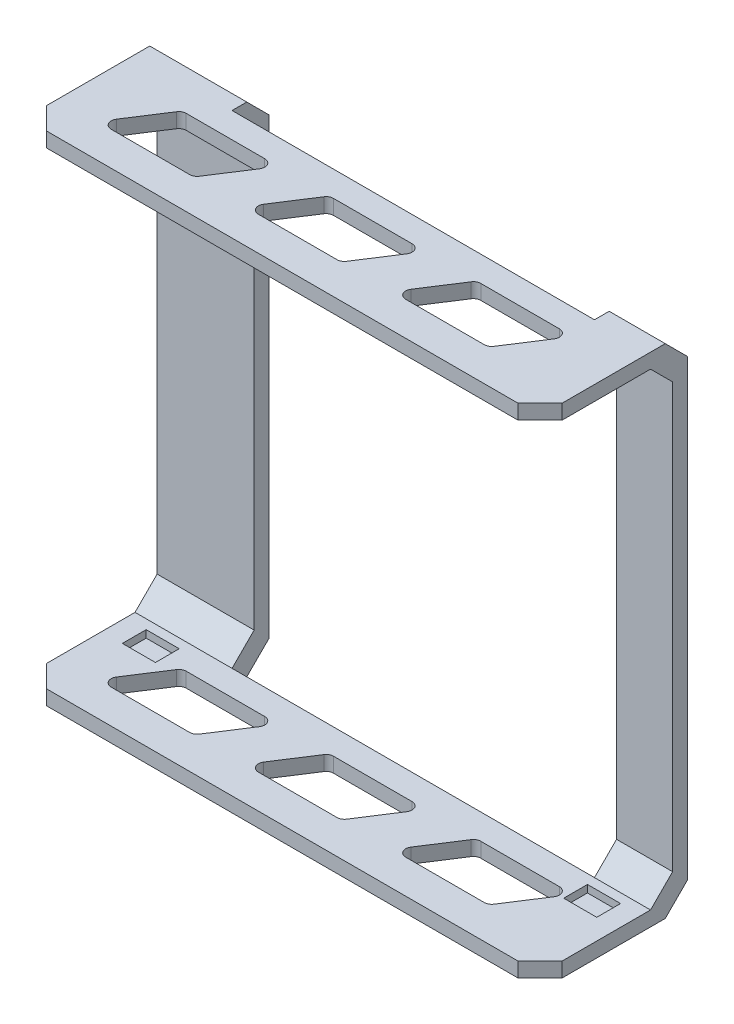
SolidWorks part; units mm, degrees
ref_plane "Front Plane" through (0, 0, 0) normal (0, 0, 1) x (1, 0, 0)
ref_plane "Top Plane" through (0, 0, 0) normal (0, 1, 0) x (1, 0, 0)
ref_plane "Right Plane" through (0, 0, 0) normal (1, 0, 0) x (0, 0, -1)
sketch "Sketch2" plane through (0, 0, 0) normal (0, 0, 1) x (1, 0, 0)
  line L1 (-34.5293, -31.742) -> (35.4707, -31.742)
  line L2 (-34.5293, -31.742) -> (-34.5293, 35.858)
  line L3 (-34.5293, 35.858) -> (35.4707, 35.858)
  line L4 (35.4707, -31.742) -> (35.4707, 35.858)
  dimension "D1" = 67.6
  dimension "D2" = 70
extrude "Boss-Extrude2" add sketch "Sketch2" along normal blind 20
sketch "Sketch3" plane through (0, 0, 0) normal (0, 0, -1) x (-1, 0, 0)
  line L1 (21.3553, 39.8277) -> (-27.8565, 39.8277)
  line L2 (21.3553, 39.8277) -> (21.3553, -33.9304)
  line L3 (21.3553, -33.9304) -> (-27.8565, -33.9304)
  line L4 (-27.8565, 39.8277) -> (-27.8565, -33.9304)
extrude "Cut-Extrude1" cut sketch "Sketch3" against normal blind 5
shell "Shell1" thickness 2
chamfer "Chamfer1" distance 3 angle 45 8 edges at (-27.9423, -29.742, 2) (31.6636, -29.742, 2) (-27.9423, 33.858, 2) (31.6636, 33.858, 2) (-27.9423, -31.742, 0) (31.6636, -31.742, 0) (31.6636, 35.858, 0) (-27.9423, 35.858, 0)
chamfer "Chamfer2" distance 3 angle 45 4 edges at (-34.5293, 34.858, 20) (-34.5293, -30.742, 20) (35.4707, 34.858, 20) (35.4707, -30.742, 20)
sketch "Sketch5" plane through (0, 35.858, 0) normal (0, 1, 0) x (1, 0, 0)
  line L0 (-29.1903, -15.4124) -> (-16.1425, -15.4124)
  line L1 (-29.1903, -15.4124) -> (-24.6803, -8.4437)
  line L2 (-16.1425, -15.4124) -> (-11.6325, -8.4437)
  line L3 (-24.6803, -8.4437) -> (-11.6325, -8.4437)
  line L4 (-9.1903, -15.4124) -> (3.8575, -15.4124)
  line L5 (-9.1903, -15.4124) -> (-4.6803, -8.4437)
  line L6 (-4.6803, -8.4437) -> (8.3675, -8.4437)
  line L7 (3.8575, -15.4124) -> (8.3675, -8.4437)
  line L8 (10.8097, -15.4124) -> (23.8575, -15.4124)
  line L9 (10.8097, -15.4124) -> (15.3197, -8.4437)
  line L10 (15.3197, -8.4437) -> (28.3675, -8.4437)
  line L11 (23.8575, -15.4124) -> (28.3675, -8.4437)
  dimension "D1" = 3
extrude "Cut-Extrude2" cut sketch "Sketch5" against normal up to next
fillet "Fillet1" radius 1 12 edges at (23.8575, 34.858, 15.4124) (10.8097, 34.858, 15.4124) (28.3675, 34.858, 8.4437) (15.3197, 34.858, 8.4437) (3.8575, 34.858, 15.4124) (8.3675, 34.858, 8.4437) (-9.1903, 34.858, 15.4124) (-4.6803, 34.858, 8.4437) (-16.1425, 34.858, 15.4124) (-11.6325, 34.858, 8.4437) (-24.6803, 34.858, 8.4437) (-29.1903, 34.858, 15.4124)
ref_plane "Plane1" through (0, 2.058, 0) normal (0, 1, 0) x (1, 0, 0)
mirror "Mirror1" about plane through (0, 2.058, 0) normal (0, 1, 0) of "Fillet1", "Cut-Extrude2"
sketch "Sketch6" plane through (0, -29.742, 0) normal (0, 1, 0) x (1, 0, 0)
  line L1 (-31.7376, -6.2787) -> (-27.2482, -6.2787)
  line L2 (-31.7376, -6.2787) -> (-31.7376, -9.5109)
  line L3 (-31.7376, -9.5109) -> (-27.2482, -9.5109)
  line L4 (-27.2482, -6.2787) -> (-27.2482, -9.5109)
extrude "Cut-Extrude3" cut sketch "Sketch6" against normal blind 1
ref_plane "Plane2" through (0.4707, 0, 0) normal (1, 0, 0) x (0, 0, -1)
mirror "Mirror2" about plane through (0, 2.058, 0) normal (0, 1, 0) of "Cut-Extrude3"
mirror "Mirror3" about plane through (0.4707, 0, 0) normal (1, 0, 0) of "Mirror2", "Cut-Extrude3"
